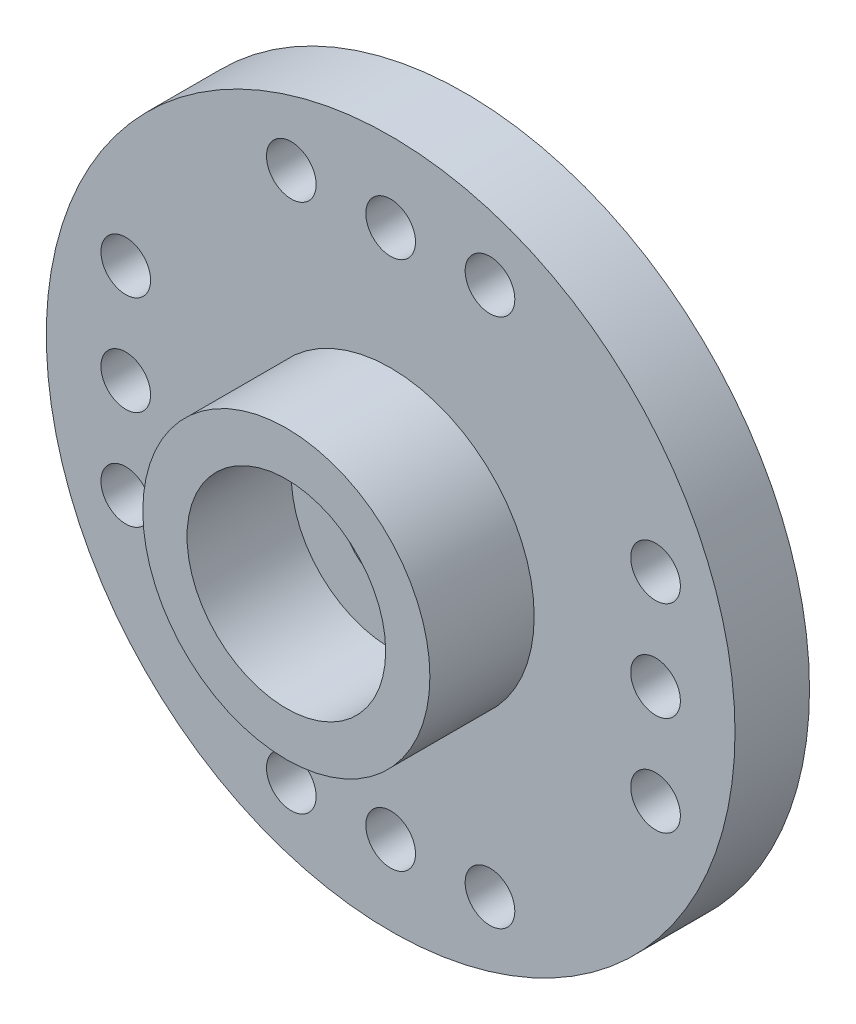
SolidWorks part; units mm, degrees
ref_plane "Front Plane" through (0, 0, 0) normal (0, 0, 1) x (1, 0, 0)
ref_plane "Top Plane" through (0, 0, 0) normal (0, 1, 0) x (1, 0, 0)
ref_plane "Right Plane" through (0, 0, 0) normal (1, 0, 0) x (0, 0, -1)
sketch "Sketch1" plane through (0, 0, 0) normal (0, 0, 1) x (1, 0, 0)
  circle A0 centre (0, 0) radius 10.4
  dimension "D1" = 20.8
extrude "Boss-Extrude1" add sketch "Sketch1" along normal blind 2.25
sketch "Sketch2" plane through (0, 0, 2.25) normal (0, 0, 1) x (1, 0, 0)
  circle A0 centre (0, 0) radius 4.335
  circle A1 centre (0, 0) radius 3
  dimension "D1" = 6
  dimension "D2" = 8.67
extrude "Boss-Extrude2" add sketch "Sketch2" along normal blind 3.15
sketch "Sketch3" plane through (0, 0, 2.25) normal (0, 0, 1) x (1, 0, 0)
  circle A0 centre (0, 0) radius 1.5
  dimension "D1" = 3
extrude "Cut-Extrude1" cut sketch "Sketch3" against normal blind 3.15
sketch "Sketch4" plane through (0, 0, 2.25) normal (0, 0, 1) x (1, 0, 0)
  circle A0 centre (0, 8) radius 0.75
  circle A1 centre (3, 8) radius 0.75
  circle A2 centre (-3, 8) radius 0.75
  circle A3 centre (8, -3) radius 0.75
  circle A4 centre (8, 0) radius 0.75
  circle A5 centre (8, 3) radius 0.75
  circle A6 centre (-3, -8) radius 0.75
  circle A7 centre (0, -8) radius 0.75
  circle A8 centre (3, -8) radius 0.75
  circle A9 centre (-8, 3) radius 0.75
  circle A10 centre (-8, 0) radius 0.75
  circle A11 centre (-8, -3) radius 0.75
  point P28 (0, 0)
  dimension "D2" = 1.5
  dimension "D3" = 1.5
  dimension "D4" = 1.5
  dimension "D1" = 8
  dimension "D5" = 3
  dimension "D6" = 3
  dimension "D7" = 4
extrude "Cut-Extrude2" cut sketch "Sketch4" against normal blind 3.15
